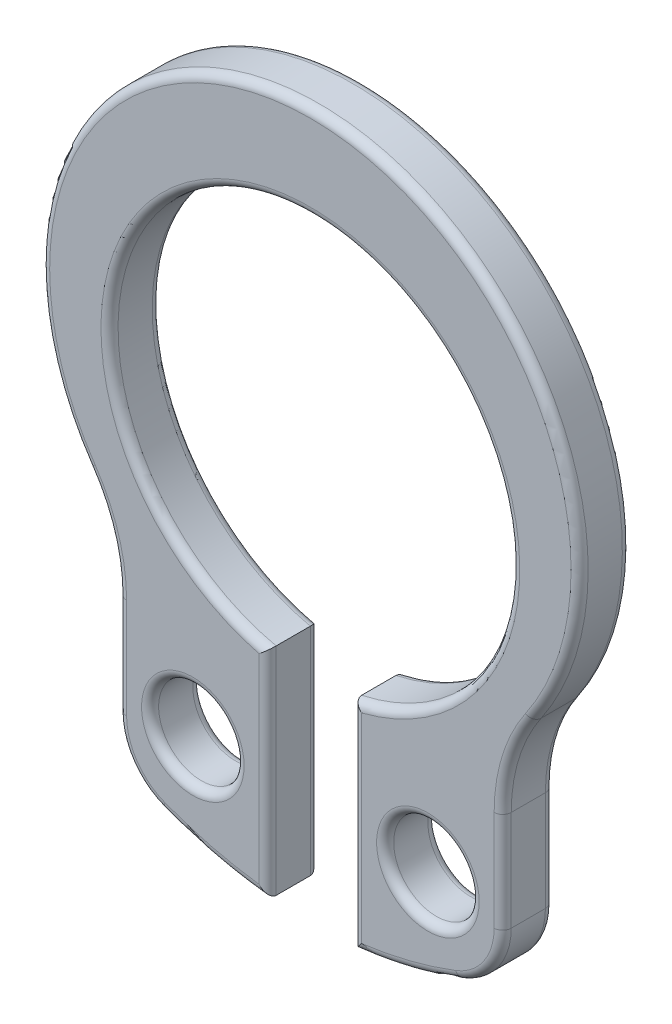
SolidWorks part; units mm, degrees
ref_plane "前视基准面" through (0, 0, 0) normal (0, 0, 1) x (1, 0, 0)
ref_plane "上视基准面" through (0, 0, 0) normal (0, 1, 0) x (1, 0, 0)
ref_plane "右视基准面" through (0, 0, 0) normal (1, 0, 0) x (0, 0, -1)
other "Configuration Table"
sketch "草图1" plane through (0, 0, 0) normal (0, 0, 1) x (1, 0, 0)
  line L0 (0, 2.35) -> (0, 3.45) construction
  circle A0 centre (0, 0) radius 2.35
  circle A1 centre (0, 0.3) radius 3.15
  dimension "D1" = 4.7
  dimension "D2" = 1.1
  dimension "D3" = 0.3
extrude "凸台-拉伸1" add sketch "草图1" along normal blind 0.6
sketch "草图2" plane through (0, 0, 0.6) normal (0, 0, 1) x (1, 0, 0)
  line L0 (0, 0) -> (0, -2.85) construction
  line L1 (2.25, -4.2965) -> (2.25, -1.9045)
  line L2 (-2.25, -4.2965) -> (-2.25, -1.9045)
  circle A0 centre (0, 0.3) radius 3.15 construction
  arc A1 (-2.25, -4.2965) -> (2.25, -4.2965) centre (0, 0) ccw
  circle A2 centre (0, 0) radius 2.35 construction
  arc A3 (-2.25, -1.9045) -> (2.25, -1.9045) centre (0, 0.3) ccw
  point P11 (0, -2.35)
  point P12 (0, -4.85)
  dimension "D1" = 2.5
  dimension "D2" = 4.5
extrude "凸台-拉伸2" add sketch "草图2" against normal blind 0.6
sketch "草图3" plane through (0, 0, 0.6) normal (0, 0, 1) x (1, 0, 0)
  line L0 (1.375, -3.6) -> (-1.375, -3.6) construction
  line L1 (0, -2.35) -> (0, -4.85) construction
  line L2 (0.5, -4.8242) -> (0.5, -2.2962)
  line L3 (-0.5, -4.8242) -> (-0.5, -2.2962)
  line L4 (0.5, -4.5902) -> (2.25, -4.5902) construction
  line L5 (2.25, -4.2965) -> (2.25, -1.9045) construction
  line L6 (1.375, -3.6) -> (1.375, -4.5902) construction
  arc A0 (-2.25, -4.2965) -> (2.25, -4.2965) centre (0, 0) ccw construction
  circle A1 centre (0, 0) radius 2.35 construction
  circle A2 centre (1.375, -3.6) radius 0.5
  circle A3 centre (-1.375, -3.6) radius 0.5
  arc A4 (-0.5, -4.8242) -> (0.5, -4.8242) centre (0, 0) ccw
  arc A5 (-0.5, -2.2962) -> (0.5, -2.2962) centre (0, 0) ccw
  point P5 (0, 0)
  point P12 (0, -3.6)
  dimension "D1" = 1
  dimension "D2" = 1
extrude "切除-拉伸1" cut sketch "草图3" against normal blind 0.6
fillet "圆角1" radius 0.8 2 edges at (-2.25, -4.2965, 0.3) (2.25, -4.2965, 0.3)
fillet "圆角2" radius 2 2 edges at (-2.25, -1.9045, 0.3) (2.25, -1.9045, 0.3)
fillet "圆角3" radius 0.1 28 edges at (2.3394, -2.0174, 0) (0, 3.45, 0) (-2.3394, -2.0174, 0) (-2.25, -3.1951, 0.6) (-2.25, -3.1951, 0) (-2.1092, -4.2348, 0) (-1.1279, -4.717, 0.6) (-1.1279, -4.717, 0) (-0.5, -3.5602, 0) (0, 2.35, 0) (0.5, -3.5602, 0) (1.1279, -4.717, 0) (1.1279, -4.717, 0.6) (2.1092, -4.2348, 0) (2.25, -3.1951, 0) (2.25, -3.1951, 0.6) (-1.875, -3.6, 0) (1.875, -3.6, 0) (0.5, -3.5602, 0.6) (0, 2.35, 0.6) (-0.5, -3.5602, 0.6) (-2.1092, -4.2348, 0.6) (-2.3394, -2.0174, 0.6) (0, 3.45, 0.6) (2.3394, -2.0174, 0.6) (2.1092, -4.2348, 0.6) (-1.875, -3.6, 0.6) (1.875, -3.6, 0.6)
